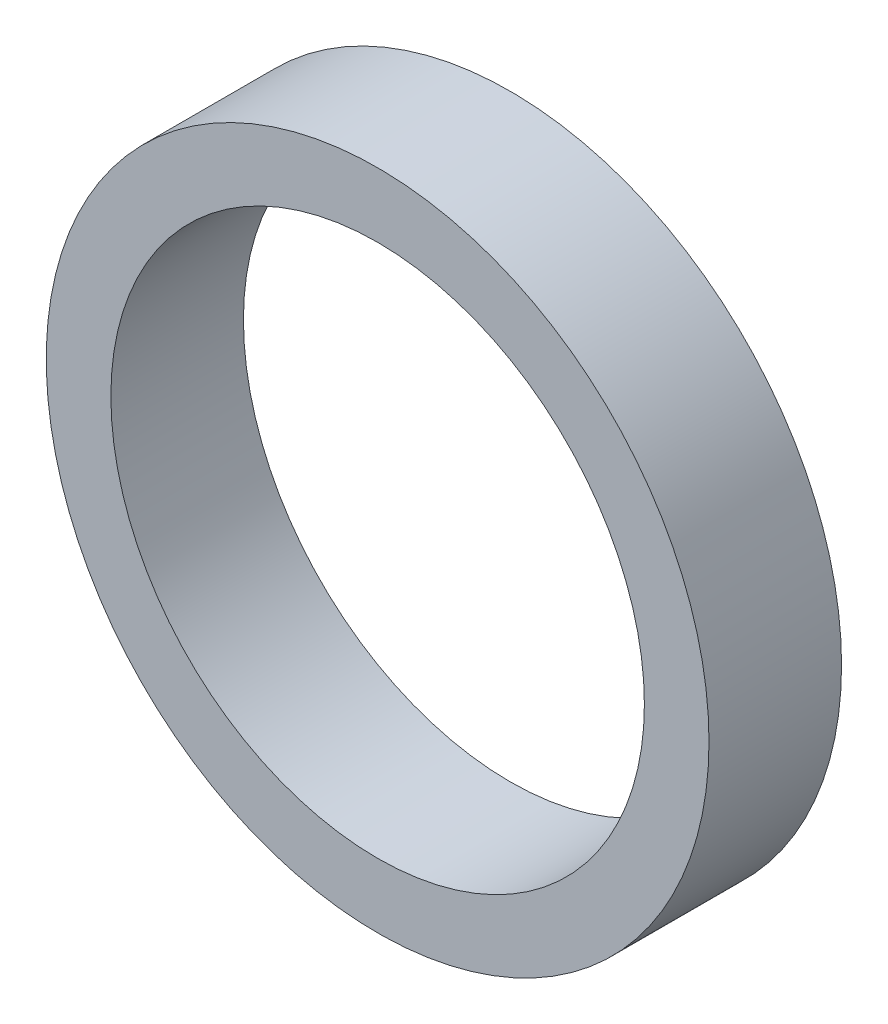
SolidWorks part; units mm, degrees
ref_plane "Front Plane" through (0, 0, 0) normal (0, 0, 1) x (1, 0, 0)
ref_plane "Top Plane" through (0, 0, 0) normal (0, 1, 0) x (1, 0, 0)
ref_plane "Right Plane" through (0, 0, 0) normal (1, 0, 0) x (0, 0, -1)
sketch "Sketch1" plane through (0, 0, 0) normal (0, 0, 1) x (1, 0, 0)
  circle A0 centre (0, 0) radius 4.025
  circle A1 centre (0, 0) radius 5
  dimension "D1" = 10
  dimension "D2" = 8.05
extrude "Boss-Extrude1" add sketch "Sketch1" along normal blind 2
